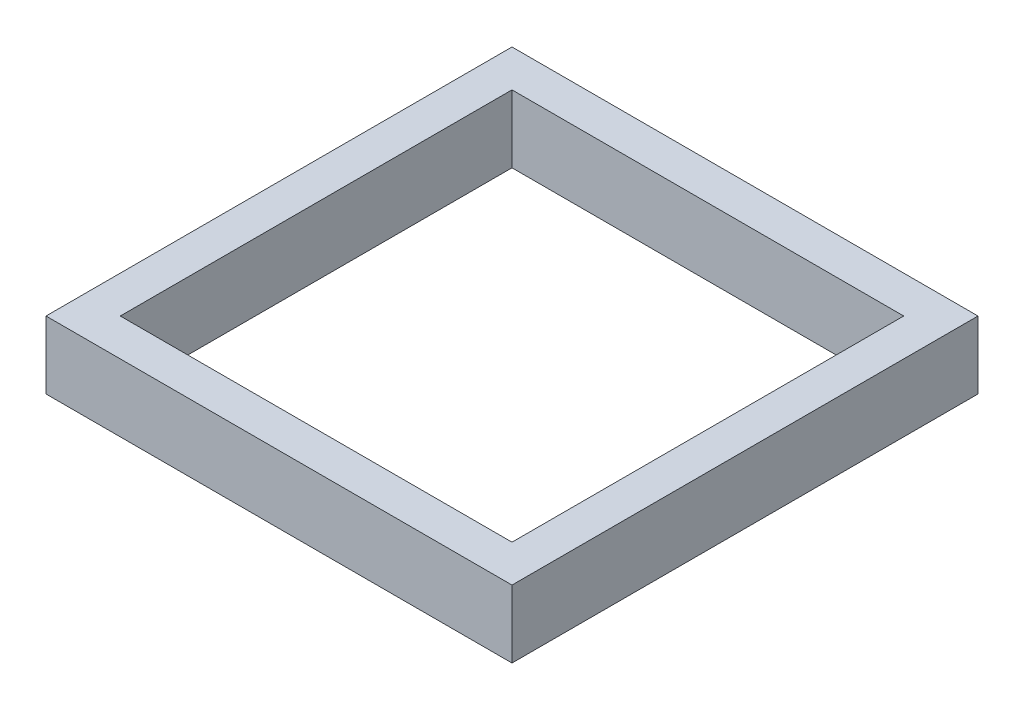
SolidWorks part; units mm, degrees
ref_plane "Front Plane" through (0, 0, 0) normal (0, 0, 1) x (1, 0, 0)
ref_plane "Top Plane" through (0, 0, 0) normal (0, 1, 0) x (1, 0, 0)
ref_plane "Right Plane" through (0, 0, 0) normal (1, 0, 0) x (0, 0, -1)
sketch "Sketch1" plane through (0, 0, 0) normal (0, 1, 0) x (1, 0, 0)
  line L1 (-368.3, 368.3) -> (368.3, 368.3)
  line L2 (-368.3, 368.3) -> (-368.3, -368.3)
  line L3 (-368.3, -368.3) -> (368.3, -368.3)
  line L4 (368.3, 368.3) -> (368.3, -368.3)
  line L5 (-368.3, 368.3) -> (368.3, -368.3) construction
  line L6 (-368.3, -368.3) -> (368.3, 368.3) construction
  line L7 (-438.15, 438.15) -> (438.15, 438.15)
  line L8 (-438.15, 438.15) -> (-438.15, -438.15)
  line L9 (-438.15, -438.15) -> (438.15, -438.15)
  line L10 (438.15, 438.15) -> (438.15, -438.15)
  line L11 (-438.15, 438.15) -> (438.15, -438.15) construction
  line L12 (-438.15, -438.15) -> (438.15, 438.15) construction
  point P0 (0, 0)
  point P6 (0, 0)
  dimension "D1" = 736.6
  dimension "D2" = 736.6
  dimension "D3" = 69.85
  dimension "D4" = 69.85
extrude "Boss-Extrude1" add sketch "Sketch1" along normal blind 127
